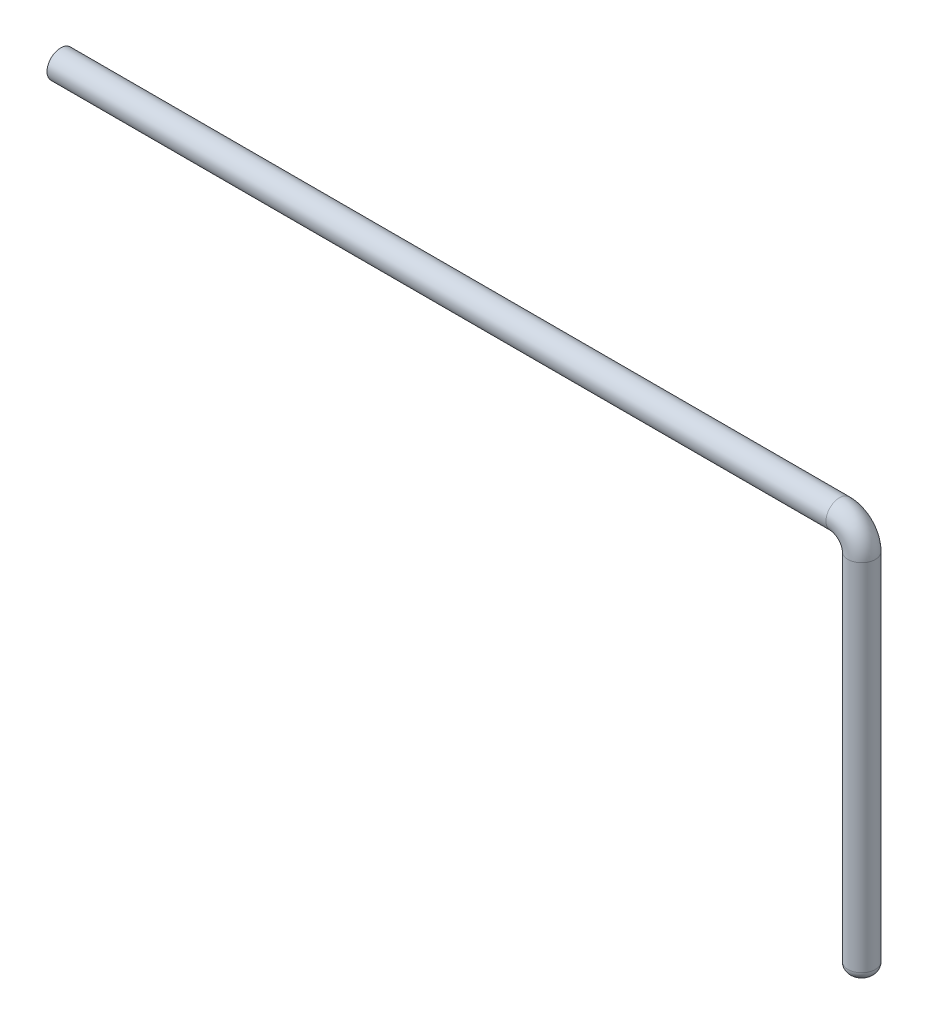
SolidWorks part; units mm, degrees
ref_plane "前视基准面" through (0, 0, 0) normal (0, 0, 1) x (1, 0, 0)
ref_plane "上视基准面" through (0, 0, 0) normal (0, 1, 0) x (1, 0, 0)
ref_plane "右视基准面" through (0, 0, 0) normal (1, 0, 0) x (0, 0, -1)
sketch "草图1" plane through (0, 0, 0) normal (0, 0, 1) x (1, 0, 0)
  line L0 (19.4019, 21.8895) -> (37.0619, 21.8895)
  line L1 (37.5619, 21.3895) -> (37.5619, 13.1395)
  arc A0 (37.5619, 21.3895) -> (37.0619, 21.8895) centre (37.0619, 21.3895) ccw
  dimension "D1" = 0.5
sweep "扫描1" add path "草图1" circular profile diameter 0.62 parameters "D3"=0.62
fillet "圆角1" radius 0.2 1 edges at (37.5619, 13.1395, 0.31)
